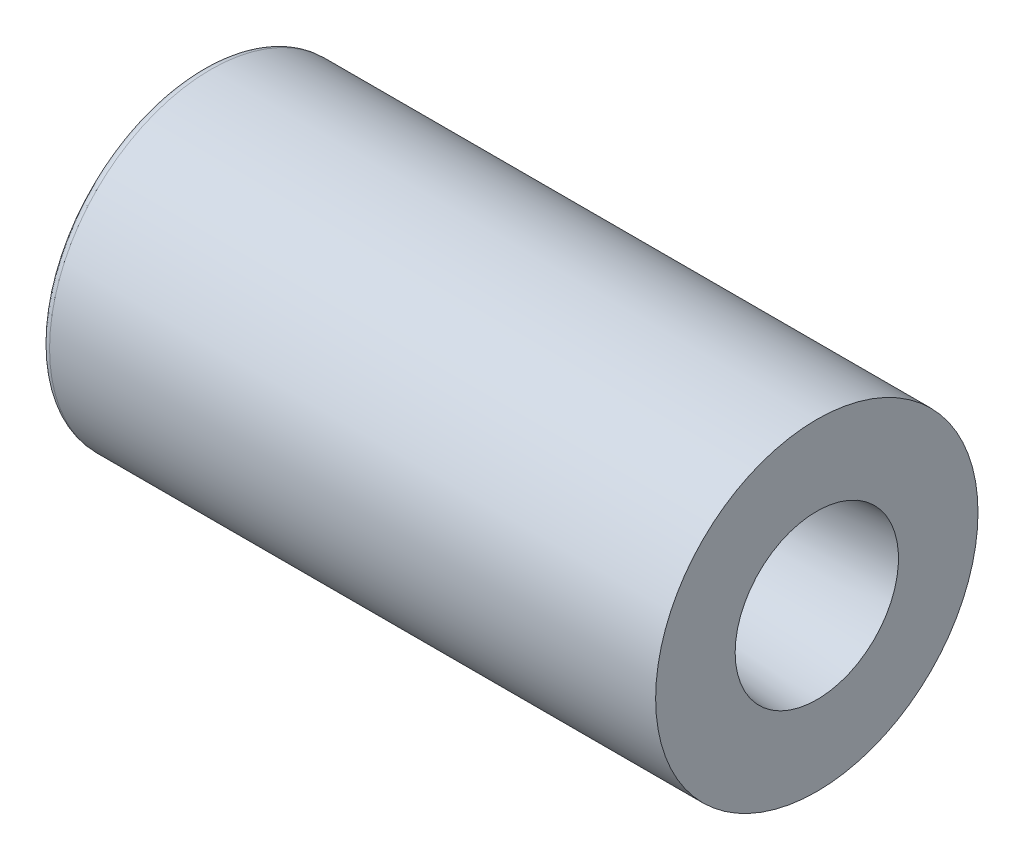
SolidWorks part; units mm, degrees
ref_plane "Front Plane" through (0, 0, 0) normal (0, 0, 1) x (1, 0, 0)
ref_plane "Top Plane" through (0, 0, 0) normal (0, 1, 0) x (1, 0, 0)
ref_plane "Right Plane" through (0, 0, 0) normal (1, 0, 0) x (0, 0, -1)
sketch "Sketch1" plane through (0, 0, 0) normal (0, 1, 0) x (1, 0, 0)
  line L0 (0, 0) -> (0, 2.286) construction
  line L1 (0, 2.286) -> (0, 5.3848)
  line L2 (0, 9.525) -> (36.3237, 9.525)
  line L3 (36.3237, 9.525) -> (36.3237, 4.826)
  line L4 (36.3237, 4.826) -> (0, 2.286)
  line L5 (0, 0) -> (36.3237, 0) construction
  line L6 (36.3237, 0) -> (36.3237, 4.826) construction
  line L7 (0, 5.3848) -> (1.905, 5.3848)
  line L8 (1.905, 5.3848) -> (1.905, 8.001)
  line L9 (1.905, 8.001) -> (0, 8.001)
  line L10 (0, 8.001) -> (0, 9.525)
  dimension "D1" = 2.286
  dimension "D2" = 4.826
  dimension "D3" = 4
  dimension "D4" = 9.525
  dimension "D5" = 5.3848
  dimension "D6" = 8.001
  dimension "D7" = 1.905
revolve "Revolve1" add sketch "Sketch1" angle 360 about L5
fillet "Fillet1" radius 0.508 1 edges at (0, 0, 9.525)
equation "\"z\" = 8\t\t\t\t'number of blades"
equation "\"de\" = 0.43in\t\t\t'entrance eye diameter"
equation "\"de_length\" = 10mm\t\t'entrance eye consistent length"
equation "\"d_exit\" = 0.18in \t\t'throat aka d1"
equation "\"d2\" = 2.1in \t\t\t'outer diameter of the impeller"
equation "\"b2\" = .2in\t\t\t'tip height from disc surface at d2; slightly higher than d_exit"
equation "\"b1\" = \"b2\" + (\"d2\"/2 - \"de\"/2)*tan(\"theta\") \t\t\t'tip height from disc surface at inlet eye"
equation "\"theta\" = 12\t\t\t'angle of blades from inner to outer "
equation "\"ae\" = 3.14*(\"de\"^2)/4\t\t'entrance eye area'"
equation "\"ce\" = 3.14*\"de\"\t\t'entrance eye circumference"
equation "\"av_ratio\" = .325\t\t'ratio of av/ae at N_s of 470, range is .275 to .375, .325 ideal. High ratio means bigger area means smaller blades"
equation "\"av\" = \"ae\"*\"av_ratio\"\t\t'area between just two blades"
equation "\"s_open\" = \"av\"/\"b1\"\t\t'width of open area"
equation "\"s\"=\"ce\" - \"z\"*\"s_open\""
equation "\"min blade thickness\" = .15in"
equation "\"bearing OD\" = 30mm"
equation "\"bearing ID\"= 10mm"
equation "\"bearing depth\"= 9mm"
equation "\"bearing outer race thickness\"= 1mm"
equation "\"bearing inner race thickness\"= 1mm"
equation "\"bearing bore\" = \"bearing depth\" + 1mm"
equation "\"lower seal OD\" = .917in\t\t'this is https://www.mcmaster.com/#9281k121/=174001b"
equation "\"lower seal ID\"= .375in"
equation "\"lower seal depth\" = .625in + .218in"
equation "\"lower seal bore\" = \"lower seal depth\" + 1mm"
equation "\"upper seal OD\" = 1.125in\t'this is https://www.mcmaster.com/#5154t33/=173zuau, needs to be visually inspected before machining!"
equation "\"upper seal ID\"= 0.625in"
equation "\"upper seal depth\"= .25in\t'aka height; these values need to be confirmed by inspection!! We may want to compress the height."
equation "\"upper seal bore\" = \"upper seal depth\" + 1mm"
equation "\"big o-ring thickness\" = .139in"
equation "\"big o-ring OD\" = 2.734in"
equation "\"big o-ring ID\" = 3.012in"
equation "\"big o-ring groove depth\" = \"big o-ring thickness\"*4/5"
equation "\"impeller center height\" = \"impeller base thickness\" + \"b1\"\t'impeller height at de"
equation "\"impeller outer height\" = \"impeller base thickness\" + \"b2\"\t'impeller height at de"
equation "\"impeller upper clearance\"= .5mm"
equation "\"impeller horizontal clearance\"= (\"d2\"*1.15 - \"d2\")/2 \t\t'clearance based on D2-D3 ratio for circular volute, ranges 1.15 to 1.2"
equation "\"impeller bottom clearance\"= .5mm"
equation "\"impeller base thickness\"= 2mm"
equation "\"impeller dowel diameter\" = 2mm"
equation "\"impeller bolt head diameter\" = \"m4 head bore diameter\""
equation "\"impeller bolt head depth\" = 4mm"
equation "\"impeller bolt stop depth\" = 3mm"
equation "\"impeller bolt bore\" = \"m4 clearance\""
equation "\"impeller shaft bore depth\" = 12mm"
equation "\"impeller shaft bore\" = 8mm"
equation "\"impeller boss depth\" = \"impeller shaft bore depth\"+\"impeller bolt stop depth\"+\"impeller bolt head depth\"-\"impeller base thickness\""
equation "\"impeller boss diameter\" = \"upper seal ID\""
equation "\"impeller dowel length\" = 2mm*2 + \"impeller shaft bore\""
equation "\"coupler motor shaft hole ID\"= 8mm"
equation "\"coupler OD\"= 17mm"
equation "\"coupler length\"= 25mm"
equation "\"motor OD\" = 64mm"
equation "\"motor shaft diameter\"= 8mm"
equation "\"motor shaft pride\"= 32mm"
equation "\"motor to bearing plate distance\" = \"motor shaft pride\" + 2mm +\"coupler length\"/2"
equation "\"square plate bolt bore\" = \"m8 clearance\""
equation "\"square plate bolt head diameter\" = 13.5mm"
equation "\"square plate bolt head depth\" = 8mm"
equation "\"square plate bolt pattern diameter\"= 3.5in"
equation "\"motor mount center bore\"= \"coupler OD\"+ 4mm"
equation "\"motor mount post radius\"= ( 3 * \"square plate bolt bore\" ) / 2"
equation "\"motor mount m4 screw hole diameter\"= 4mm"
equation "\"motor mount m4 head diameter\"= 7.25mm"
equation "\"motor mount m4 head depth\"= 4mm"
equation "\"motor mount m4 pattern diamater\" = 30mm"
equation "\"motor mount plate thickness\"= 8mm + \"motor mount m4 head depth\""
equation "\"bearing plate stop ID\" = \"bearing OD\" - 4mm"
equation "\"bearing plate stop depth\" = 3mm"
equation "\"bearing plate thickness\" = \"bearing bore\" + \"bearing plate stop depth\" + \"shaft bearing stop length\""
equation "\"lower seal plate lip depth\" = 2mm"
equation "\"lower seal plate lip ID\" = \"lower seal OD\" - 3mm"
equation "\"lower seal plate thickness\" = \"lower seal plate lip depth\" + \"lower seal bore\""
equation "\"shaft coupler section diameter\" = 8mm"
equation "\"shaft coupler section length\" = \"motor to bearing plate distance\" - \"motor shaft pride\" - 2mm"
equation "\"shaft bearing section diameter\" = \"bearing ID\""
equation "\"shaft bearing section length\" = \"bearing plate stop depth\" + \"bearing depth\""
equation "\"shaft bearing stop diameter\" = \"bearing ID\" + 4mm"
equation "\"shaft bearing stop length\" = 3mm"
equation "\"shaft lower seal section diameter\" = \"lower seal ID\""
equation "\"shaft lower seal section length\" = \"lower seal plate thickness\" + 1mm"
equation "\"shaft impeller section diameter\" = \"impeller shaft bore\""
equation "\"shaft impeller section length\" = \"upper seal plate thickness\" + \"upper seal plate riser\" + \"impeller bottom clearance\" + \"impeller base thickness\" - \"impeller bolt head depth\" - \"impeller bolt stop depth\""
equation "\"upper seal plate thickness\" = \"upper seal plate pressure hole diameter\"+10mm"
equation "\"upper seal plate lip ID\" = \"upper seal OD\" - 3mm"
equation "\"upper seal plate riser\" = 6.59mm \t\t'this number needs to be read from the housing file"
equation "\"upper seal plate pressure hole diameter\" = .125in\t'this is 1/8 drill "
equation "\"upper seal plate pressure tap diameter\" = .328125in \t'this is 21/64 drill for a 1/8 ANPT tap"
equation "\"upper seal plate pressure tap grip\" = 5mm\t\t'this is the area around the tap so it doesn't crack"
equation "\"upper seal plate pressure tap depth\" = 12"
equation "\"impeller cavity center height\"= \"impeller bottom clearance\" + \"impeller upper clearance\" + \"impeller center height\""
equation "\"impeller cavity diameter\"= 2 * \"impeller horizontal clearance\" + \"d2\" \t\t\t\t\t\t\t\t\t'called D3 analytically"
equation "\"impeller cavity outer height\"= \"impeller bottom clearance\" + \"impeller upper clearance\" + \"impeller base thickness\" + \"b2\" \t\t'this is height at impeller diameter d2, not at d3"
equation "\"impeller housing thickness\"= \"impeller housing exit threaded diameter\" + 2*\"impeller housing outlet grip\""
equation "\"impeller housing diameter\" = \"square plate bolt pattern diameter\" + 2*\"motor mount post radius\""
equation "\"impeller housing bolt count\" = 8"
equation "\"impeller housing bolt diameter\" = \"m6 clearance\""
equation "\"impeller housing bolt pattern diameter\" = 3.5in"
equation "\"impeller housing threaded inlet diameter\" = 0.515625in \t'this is the 33/64 drill size for 9/16-18 fitting, expecting swagelok SS-8FK0-1-6STH fitting"
equation "\"impeller housing threaded inlet depth\"= 10mm"
equation "\"impeller housing exit threaded diameter\"= 0.515625in \t\t'this is the 33/64 drill size for 9/16-18 fitting, expecting swagelok SS-8FK0-1-6STH fitting"
equation "\"impeller housing exit threaded depth\"= 10mm"
equation "\"impeller housing diffuser conical angle\"=10"
equation "\"impeller housing diffuser tangent angle\"=5"
equation "\"impeller housing diffuser final diameter\" = .38in\t\t'aka d2'"
equation "\"impeller housing outlet grip\" = 5mm"
equation "\"end mill size\" = 0.375in\t'for 3/8 endmill"
equation "\"m4 clearance\" = 0.171875in \t'this is 11/64 bit for 4.36mm"
equation "\"m4 tap\" = 0.125in\t\t'this is 1/8 bit for 3.17mm"
equation "\"m4 head bore diameter\" = 7.5mm"
equation "\"m4 head bore depth\" = 5mm\t'actual is ~4mm"
equation "\"m6 clearance\" = 0.234375in\t'this is 15/64 bit = 5.95mm, could use 6mm bit, B bit for 6.04mm or 1/4 bit for 6.35mm"
equation "\"m6 tap\" = 5mm\t\t\t'5mm is appropriate, could use 13/64 or #5,6,7"
equation "\"m6 head bore diameter\" = 11mm\t\t"
equation "\"m6 head bore depth\" = 7mm\t'actual is 6mm"
equation "\"m8 clearance\" = 0.3125in\t'this is 5/16in for 7.93mm, could use 8mm, O,P, or 21/64"
equation "\"m8 tap\" = 0.265625in\t\t'this is 17/64 for 6.746875mm"
equation "\"m8 head bore diameter\" = 14mm"
equation "\"m8 head bore depth\" = 9mm\t'actual is 8mm"
equation "\"D1@Sketch1\"=\"d_exit\"/2"
equation "\"D2@Sketch1\"=\"impeller housing diffuser final diameter\"/2"
equation "\"diffuser cartridge OD\" =.75in"
equation "\"D4@Sketch1\"=\"diffuser cartridge OD\"/2"
